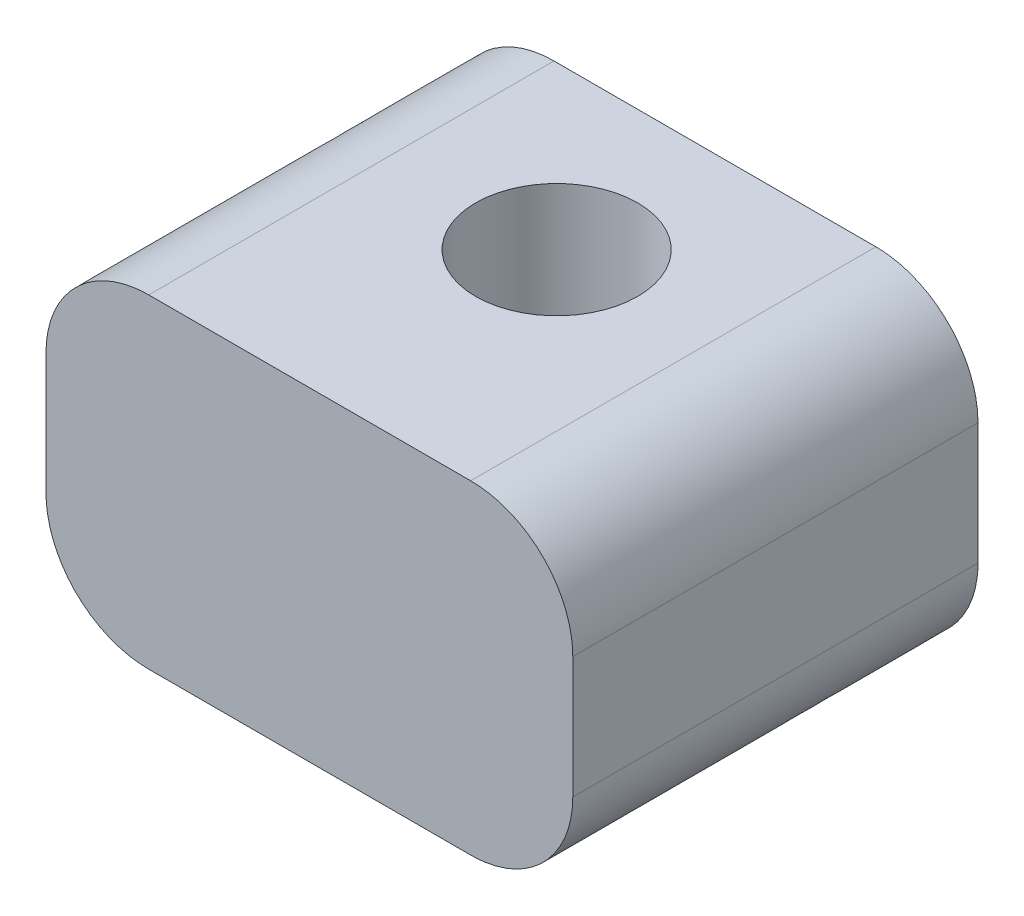
SolidWorks part; units mm, degrees
ref_plane "Plan de face" through (0, 0, 0) normal (0, 0, 1) x (1, 0, 0)
ref_plane "Plan de dessus" through (0, 0, 0) normal (0, 1, 0) x (1, 0, 0)
ref_plane "Plan de droite" through (0, 0, 0) normal (1, 0, 0) x (0, 0, -1)
sketch "Esquisse1" plane through (0, 0, 0) normal (0, 0, 1) x (1, 0, 0)
  line L0 (38.7855, 40.6141) -> (-40.6517, 40.6141)
  line L1 (-40.6517, -39.3859) -> (38.7855, -39.3859)
  line L2 (-66.0178, 15.6141) -> (-66.0178, -14.3859)
  line L3 (63.9822, -14.3859) -> (63.9822, 15.6141)
  spline S0 degree 3 poles (-40.6517, 40.6141) (-42.3144, 40.6141) (-43.95, 40.4545) (-46.3643, 39.9852) (-47.1625, 39.7902) (-48.7455, 39.3212) (-49.5335, 39.0456) (-51.8287, 38.1155) (-53.2814, 37.3559) (-55.3454, 36.0087) (-56.0141, 35.5248) (-57.3112, 34.4845) (-57.9289, 33.9366) (-59.6913, 32.2135) (-60.7465, 30.9591) (-62.1457, 28.9152) (-62.5826, 28.2035) (-63.3749, 26.7553) (-63.7328, 26.0159) (-64.3733, 24.5068) (-64.6559, 23.7372) (-65.1449, 22.1674) (-65.3517, 21.3656) (-65.851, 18.9232) (-66.0178, 17.2774) (-66.0178, 15.6141) knots 0 0 0 0 0.125 0.125 0.1875 0.1875 0.25 0.25 0.375 0.375 0.4375 0.4375 0.5 0.5 0.625 0.625 0.6875 0.6875 0.75 0.75 0.8125 0.8125 0.875 0.875 1 1 1 1
  spline S1 degree 3 poles (-66.0178, -14.3859) (-66.0178, -16.0489) (-65.8511, -17.6833) (-65.3617, -20.0941) (-65.1584, -20.8909) (-64.6695, -22.4703) (-64.383, -23.2539) (-63.4189, -25.5311) (-62.6329, -26.97) (-61.4734, -28.6704) (-61.2326, -29.0056) (-60.7328, -29.6658) (-60.4732, -29.9916) (-59.6752, -30.9436) (-59.1156, -31.5475) (-57.3566, -33.2698) (-56.0777, -34.2996) (-54.3434, -35.4353) (-53.9899, -35.6547) (-53.2767, -36.0734) (-52.9162, -36.2733) (-51.8231, -36.8456) (-50.3347, -37.5353) (-48.7852, -38.0799) (-47.2049, -38.551) (-46.3956, -38.7503) (-43.9577, -39.2265) (-42.314, -39.3859) (-40.6517, -39.3859) knots 0 0 0 0 0.125 0.125 0.1875 0.1875 0.25 0.25 0.375 0.375 0.40625 0.40625 0.4375 0.4375 0.5 0.5 0.625 0.625 0.65625 0.65625 0.6875 0.6875 0.75 0.8125 0.8125 0.875 0.875 1 1 1 1
  spline S2 degree 3 poles (38.7855, -39.3859) (40.4427, -39.3859) (42.0725, -39.2254) (44.4779, -38.7532) (45.2731, -38.557) (46.85, -38.0851) (47.6344, -37.808) (49.9178, -36.8733) (51.3625, -36.1103) (53.4143, -34.7577) (54.0799, -34.271) (55.3664, -33.2286) (55.9787, -32.68) (57.7259, -30.9545) (58.7717, -29.6987) (60.1578, -27.6532) (60.5896, -26.9422) (61.3723, -25.4968) (62.0795, -24.0208) (62.638, -22.4845) (63.1211, -20.9176) (63.3256, -20.1162) (63.8177, -17.6832) (63.9822, -16.0434) (63.9822, -14.3859) knots 0 0 0 0 0.125 0.125 0.1875 0.1875 0.25 0.25 0.375 0.375 0.4375 0.4375 0.5 0.5 0.625 0.625 0.6875 0.6875 0.75 0.8125 0.8125 0.875 0.875 1 1 1 1
  spline S3 degree 3 poles (63.9822, 15.6141) (63.9822, 17.2713) (63.8178, 18.9005) (63.3348, 21.304) (63.1341, 22.0984) (62.6516, 23.6734) (62.3685, 24.4555) (61.4156, 26.7293) (60.6385, 28.1665) (59.4915, 29.8658) (59.2532, 30.2007) (58.7587, 30.8607) (58.5017, 31.1865) (57.7105, 32.1401) (57.1555, 32.7451) (55.4107, 34.4707) (54.1418, 35.5028) (52.4205, 36.6417) (52.0688, 36.8621) (51.3592, 37.283) (51.0004, 37.484) (49.9126, 38.0593) (48.4315, 38.7524) (46.8897, 39.2998) (45.3171, 39.7733) (44.5117, 39.9738) (42.081, 40.4535) (40.4424, 40.6141) (38.7855, 40.6141) knots 0 0 0 0 0.125 0.125 0.1875 0.1875 0.25 0.25 0.375 0.375 0.40625 0.40625 0.4375 0.4375 0.5 0.5 0.625 0.625 0.65625 0.65625 0.6875 0.6875 0.75 0.8125 0.8125 0.875 0.875 1 1 1 1
extrude "Boss.-Extru.1" add sketch "Esquisse1" against normal blind 100 from offset 80
sketch "Esquisse3" plane through (0, 0, -20) normal (0, 0, -1) x (-1, 0, 0)
  line L0 (50.4849, -8.2739) -> (-49.5151, -8.2739)
  line L1 (50.4849, -8.2739) -> (50.4849, 7.7261)
  line L2 (50.4849, 7.7261) -> (-49.5151, 7.7261)
  line L3 (-49.5151, -8.2739) -> (-49.5151, 7.7261)
  dimension "D1" = 100
  dimension "D2" = 16
extrude "Enlèv. mat.-Extru.1" cut sketch "Esquisse3" along normal blind 80 from offset 80 offset against normal yes
fillet "Congé4" radius 11 2 edges at (49.5151, -0.2739, 60) (-50.4849, -0.2739, 60)
sketch "Esquisse4" plane through (0, -39.3859, 0) normal (0, -1, 0) x (1, 0, 0)
  line L0 (0, -38.5057) -> (0, 153.5884) construction
  line L1 (-40.6517, -20) -> (38.7855, -20) construction
  circle A0 centre (0, 20) radius 20
  dimension "D1" = 40
  dimension "D2" = 40
extrude "Enlèv. mat.-Extru.2" cut sketch "Esquisse4" along direction (0, 1, 0) on the side against the normal through all
